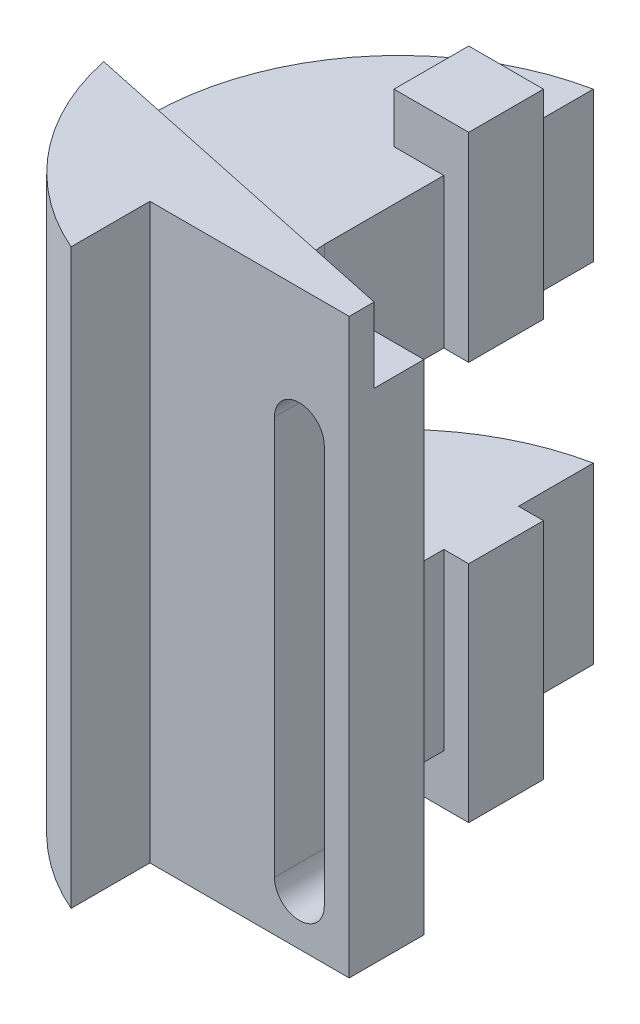
SolidWorks part; units mm, degrees
material "1060 Alloy"
ref_plane "Front Plane" through (0, 0, 0) normal (0, 0, 1) x (1, 0, 0)
ref_plane "Top Plane" through (0, 0, 0) normal (0, 1, 0) x (1, 0, 0)
ref_plane "Right Plane" through (0, 0, 0) normal (1, 0, 0) x (0, 0, -1)
sketch "Sketch1" plane through (0, 0, 0) normal (0, 1, 0) x (1, 0, 0)
  line L0 (0, 0) -> (-40, 0)
  line L1 (-20, 0) -> (-20, 30) construction
  line L2 (-30, 15) -> (0, 15)
  line L3 (0, 15) -> (0, 0)
  line L4 (-40, 0) -> (-40, -15.8258)
  line L5 (-30, 15) -> (-30, 48.9898)
  line L6 (-30, 63.9898) -> (-25, 63.9898)
  line L7 (-25, 63.9898) -> (-25, 48.9898)
  line L8 (-25, 48.9898) -> (-30, 48.9898)
  line L9 (-30, 63.9898) -> (-30, 78.9898)
  arc A0 (-30, 78.9898) -> (-40, -15.8258) centre (-20, 30) ccw
  dimension "D3" = 100
  dimension "D1" = 40
  dimension "D2" = 30
  dimension "D4" = 15
  dimension "D5" = 15
  dimension "D6" = 5
extrude "Boss-Extrude1" add sketch "Sketch1" along normal blind 125
sketch "Sketch2" plane through (0, 0, 0) normal (0, -1, 0) x (1, 0, 0)
  line L0 (-30, -63.9898) -> (-40, -63.9898)
  line L1 (-30, -48.9898) -> (-40, -48.9898)
  line L2 (-40, -48.9898) -> (-40, -63.9898)
  line L3 (-30, -63.9898) -> (-30, -78.9898)
  line L4 (-30, -63.9898) -> (-30, -78.9898) construction
  line L5 (-30, -48.9898) -> (-30, -15)
  line L6 (-30, -15) -> (0, -15)
  line L7 (0, -15) -> (0, 0)
  line L8 (0, 0) -> (-40, 0)
  line L9 (-40, 0) -> (-40, 15.8258)
  arc A0 (-40, 15.8258) -> (-30, -78.9898) centre (-20, -30) ccw
  dimension "D1" = 10
extrude "Cut-Extrude1" cut sketch "Sketch2" against normal blind 10
sketch "Sketch3" plane through (0, 125, 0) normal (0, 1, 0) x (1, 0, 0)
  line L0 (0, 5) -> (-63.3013, 5)
  line L1 (0, 0) -> (0, 15) construction
  line L2 (0, 5) -> (0, 15)
  line L3 (0, 15) -> (-30, 15) construction
  line L4 (0, 15) -> (-30, 15)
  line L5 (-30, 15) -> (-30, 48.9898)
  line L6 (-30, 48.9898) -> (-25, 48.9898)
  line L7 (-25, 48.9898) -> (-25, 63.9898)
  line L8 (-25, 63.9898) -> (-30, 63.9898)
  line L9 (-30, 63.9898) -> (-30, 78.9898)
  arc A0 (-30, 78.9898) -> (-40, -15.8258) centre (-20, 30) ccw construction
  arc A1 (-30, 78.9898) -> (-63.3013, 5) centre (-20, 30) ccw
  dimension "D1" = 5
extrude "Cut-Extrude2" cut sketch "Sketch3" against normal blind 5
sketch "Sketch4" plane through (0, 120, 0) normal (0, 1, 0) x (1, 0, 0)
  line L0 (-30, 63.9898) -> (-40, 63.9898)
  line L1 (-30, 48.9898) -> (-40, 48.9898)
  line L2 (-40, 48.9898) -> (-40, 63.9898)
  line L3 (-30, 63.9898) -> (-30, 78.9898)
  line L4 (-30, 48.9898) -> (-30, 15)
  line L5 (-30, 15) -> (0, 15)
  line L6 (0, 15) -> (0, 5)
  line L7 (0, 5) -> (-63.3013, 5)
  arc A0 (-30, 78.9898) -> (-63.3013, 5) centre (-20, 30) ccw
  dimension "D1" = 10
extrude "Cut-Extrude3" cut sketch "Sketch4" against normal blind 10
fillet "Fillet1" radius 10 1 edges at (-30, 60, -15)
sketch "Sketch6" plane through (-30, 0, 0) normal (1, 0, 0) x (0, 0, -1)
  line L0 (78.9898, 80) -> (78.9898, 45)
  line L1 (78.9898, 110) -> (78.9898, 10) construction
  line L2 (78.9898, 45) -> (38.9898, 45)
  line L3 (38.9898, 45) -> (38.9898, 80)
  line L4 (38.9898, 80) -> (78.9898, 80)
  dimension "D1" = 35
  dimension "D2" = 30
  dimension "D3" = 40
extrude "Cut-Extrude5" cut sketch "Sketch6" against normal through all both and the other way through all
sketch "Sketch7" plane through (0, 110, 0) normal (0, 1, 0) x (1, 0, 0)
  line L0 (0, 5) -> (-68.9168, 19.6487)
  line L1 (0, 5) -> (0, 15) construction
  line L2 (0, 5) -> (-63.3013, 5)
  arc A0 (-30, 78.9898) -> (-63.3013, 5) centre (-20, 30) ccw construction
  arc A1 (-68.9168, 19.6487) -> (-63.3013, 5) centre (-20, 30) ccw
  dimension "D1" = 78
extrude "Boss-Extrude2" add sketch "Sketch7" along normal blind 15
sketch "Sketch8" plane through (0, 0, -15) normal (0, 0, -1) x (-1, 0, 0)
  line L1 (0, 110) -> (0, 10) construction
  line L3 (15, 100) -> (15, 20)
  line L4 (5, 100) -> (5, 20)
  circle A0 centre (10, 100) radius 5
  circle A1 centre (10, 20) radius 5
  dimension "D2" = 10
  dimension "D1" = 10
  dimension "D3" = 10
  dimension "D4" = 80
  dimension "D5" = 80
extrude "Cut-Extrude6" cut sketch "Sketch8" against normal through all both contours L4 A1 L3 A0 | A0 | A1
